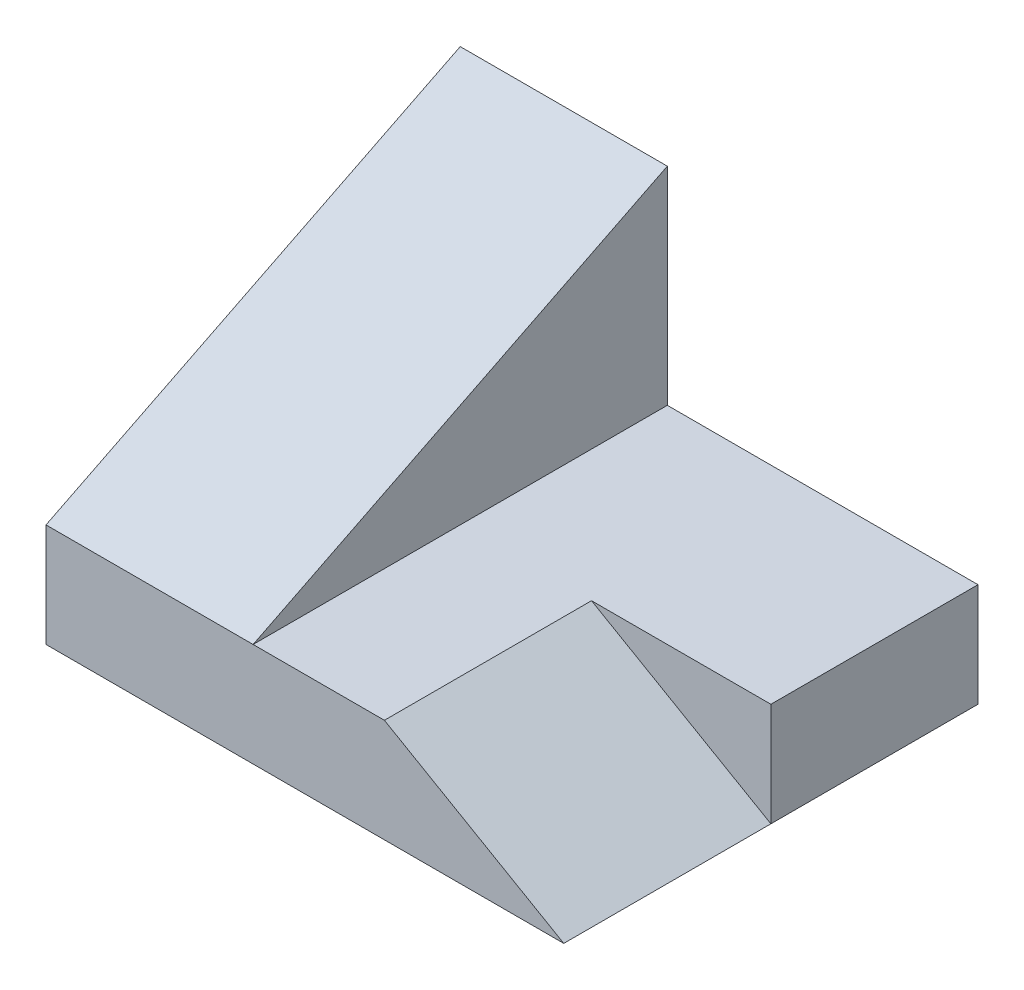
SolidWorks part; units mm, degrees
ref_plane "Front Plane" through (0, 0, 0) normal (0, 0, 1) x (1, 0, 0)
ref_plane "Top Plane" through (0, 0, 0) normal (0, 1, 0) x (1, 0, 0)
ref_plane "Right Plane" through (0, 0, 0) normal (1, 0, 0) x (0, 0, -1)
sketch "Sketch1" plane through (0, 0, 0) normal (0, 1, 0) x (1, 0, 0)
  line L1 (-25, 20) -> (25, 20)
  line L2 (-25, 20) -> (-25, -20)
  line L3 (-25, -20) -> (25, -20)
  line L4 (25, 20) -> (25, -20)
  line L5 (-25, 20) -> (25, -20) construction
  line L6 (-25, -20) -> (25, 20) construction
  point P0 (0, 0)
  dimension "D1" = 50
  dimension "D2" = 40
extrude "Boss-Extrude1" add sketch "Sketch1" along normal blind 10
sketch "Sketch2" plane through (0, 0, 20) normal (0, 0, 1) x (1, 0, 0)
  line L0 (25, 0) -> (7.6795, 10)
  line L1 (-25, 10) -> (25, 10) construction
  line L2 (7.6795, 10) -> (25, 10)
  line L3 (25, 10) -> (25, 0)
  dimension "D1" = 20
extrude "Cut-Extrude1" cut sketch "Sketch2" against normal blind 20
sketch "Sketch3" plane through (0, 10, 0) normal (0, 1, 0) x (1, 0, 0)
  line L0 (-25, -20) -> (7.6795, -20) construction
  line L1 (-25, 20) -> (-5, 20)
  line L2 (-25, 20) -> (-25, -20)
  line L3 (-25, -20) -> (-5, -20)
  line L4 (-5, 20) -> (-5, -20)
  dimension "D1" = 20
extrude "Boss-Extrude2" add sketch "Sketch3" along normal blind 20
sketch "Sketch4" plane through (-5, 0, 0) normal (1, 0, 0) x (0, 0, -1)
  line L0 (20, 30) -> (-20, 10)
  line L1 (-20, 10) -> (-20, 30)
  line L2 (-20, 30) -> (20, 30)
extrude "Cut-Extrude2" cut sketch "Sketch4" against normal blind 20
